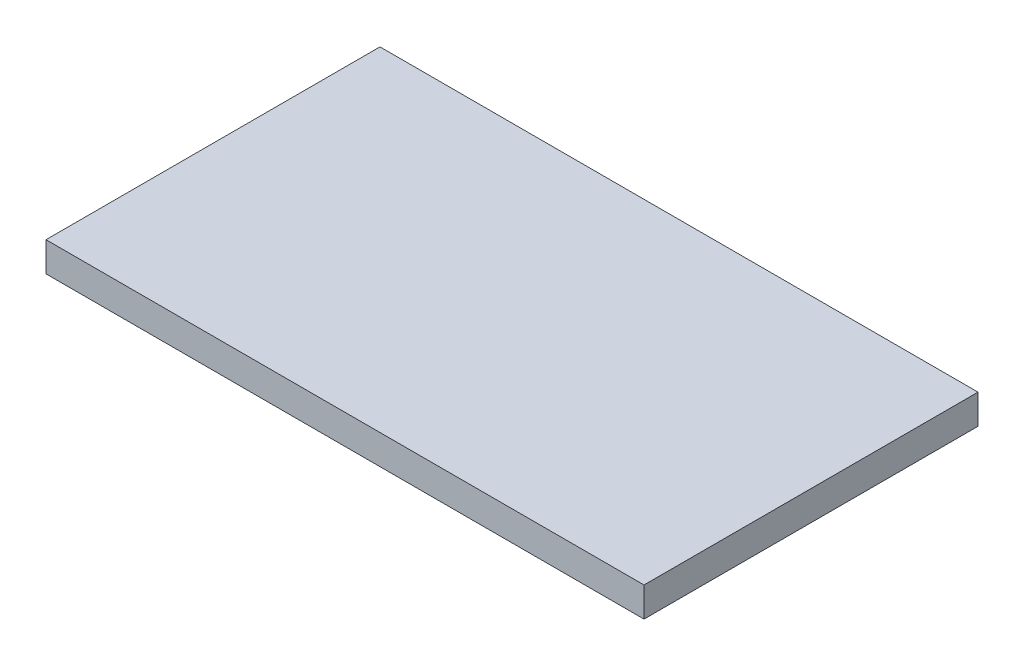
SolidWorks part; units mm, degrees
ref_plane "Front Plane" through (0, 0, 0) normal (0, 0, 1) x (1, 0, 0)
ref_plane "Top Plane" through (0, 0, 0) normal (0, 1, 0) x (1, 0, 0)
ref_plane "Right Plane" through (0, 0, 0) normal (1, 0, 0) x (0, 0, -1)
sketch "Sketch1" plane through (0, 0, 0) normal (0, 0, 1) x (1, 0, 0)
  line L2 (-161.15, -33.1) -> (161.15, -33.1) construction
  line L4 (-161.15, -33.1) -> (-202.3373, -33.1)
  line L5 (-161.15, -33.1) -> (161.15, -33.1)
  line L10 (-202.3373, -53.1315) -> (202.3375, -53.1315)
  line L16 (161.15, -33.1) -> (202.3375, -33.1)
  line L19 (-202.3373, -33.1) -> (-202.3373, -53.1315)
  line L20 (202.3375, -33.1) -> (202.3375, -53.1315)
extrude "Boss-Extrude1" add sketch "Sketch1" along normal up to surface (226 mm away)
